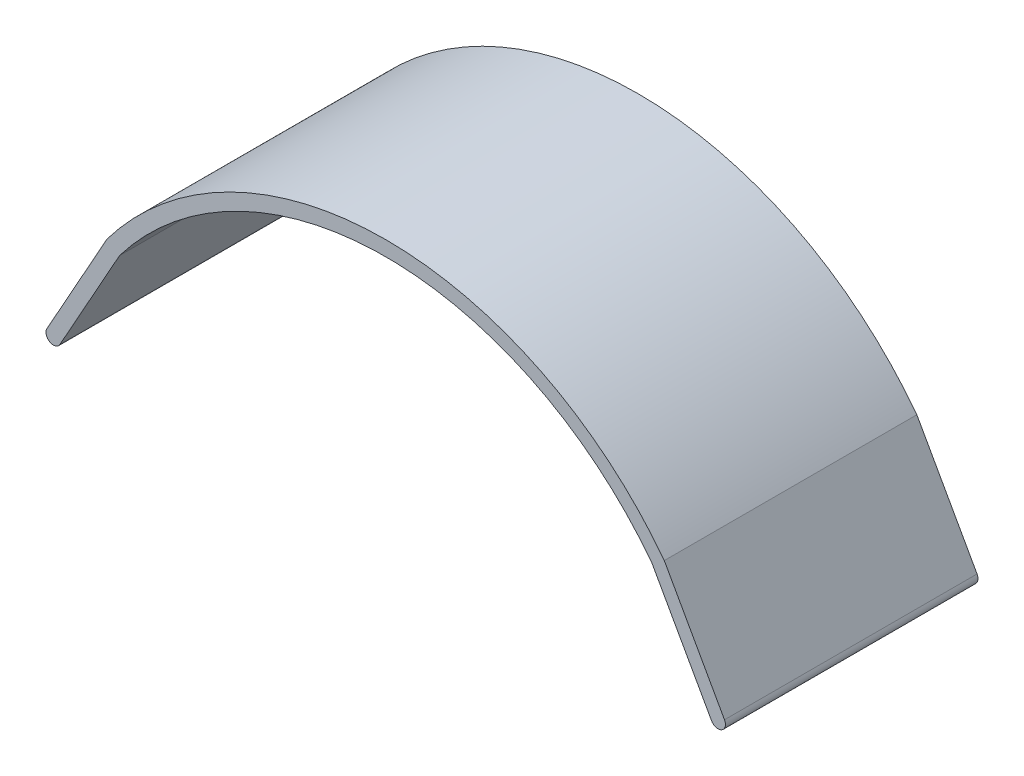
SolidWorks part; units mm, degrees
ref_plane "Front Plane" through (0, 0, 0) normal (0, 0, 1) x (1, 0, 0)
ref_plane "Top Plane" through (0, 0, 0) normal (0, 1, 0) x (1, 0, 0)
ref_plane "Right Plane" through (0, 0, 0) normal (1, 0, 0) x (0, 0, -1)
sketch "Sketch2" plane through (0, 0, 0) normal (0, 0, 1) x (1, 0, 0)
  line L0 (102.5, 31.3328) -> (110.606, 16.8196) construction
  line L1 (19.394, 16.8196) -> (27.5, 31.3328) construction
  line L2 (102.5, 31.3328) -> (110.606, 16.8196)
  line L3 (19.394, 16.8196) -> (27.5, 31.3328)
  line L4 (100.8219, 30.2359) -> (108.8598, 15.8443)
  line L5 (21.1402, 15.8443) -> (29.1781, 30.2359)
  line L6 (19.394, 16.8196) -> (20.2671, 16.3319) construction
  line L7 (65, 48) -> (65, 5.2022) construction
  arc A0 (102.5, 31.3328) -> (27.5, 31.3328) centre (65, 3) ccw construction
  arc A1 (102.5, 31.3328) -> (27.5, 31.3328) centre (65, 3) ccw
  arc A2 (100.8219, 30.2359) -> (29.1781, 30.2359) centre (65, 3) ccw
  arc A3 (19.394, 16.8196) -> (21.1402, 15.8443) centre (20.2671, 16.3319) ccw
  arc A4 (110.606, 16.8196) -> (108.8598, 15.8443) centre (109.7329, 16.3319) cw
  dimension "D2" = 1
  dimension "D1" = 2
extrude "Boss-Extrude1" add sketch "Sketch2" along normal blind 2 and the other way blind 32
